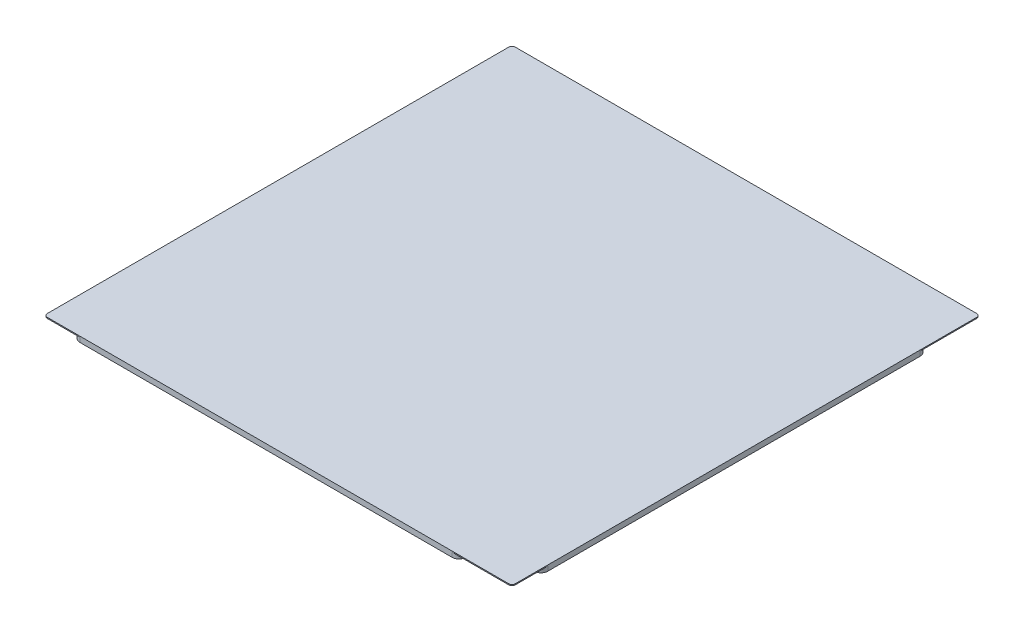
SolidWorks part; units mm, degrees
material "Kapton"
ref_plane "Front Plane" through (0, 0, 0) normal (0, 0, 1) x (1, 0, 0)
ref_plane "Top Plane" through (0, 0, 0) normal (0, 1, 0) x (1, 0, 0)
ref_plane "Right Plane" through (0, 0, 0) normal (1, 0, 0) x (0, 0, -1)
sketch "Sketch1" plane through (0, 0, 0) normal (0, 1, 0) x (1, 0, 0)
  line L1 (-68.5, -68.5) -> (68.5, -68.5)
  line L2 (-68.5, -68.5) -> (-68.5, 68.5)
  line L3 (-68.5, 68.5) -> (68.5, 68.5)
  line L4 (68.5, -68.5) -> (68.5, 68.5)
  line L5 (-68.5, -68.5) -> (68.5, 68.5) construction
  line L6 (-68.5, 68.5) -> (68.5, -68.5) construction
  point P0 (0, 0)
  dimension "D1" = 137
extrude "Boss-Extrude1" add sketch "Sketch1" along normal mid plane 0.3
sketch "Sketch2" plane through (0, -0.15, 0) normal (0, -1, 0) x (1, 0, 0)
  line L0 (70, -68.5) -> (50, -68.5) construction
  line L1 (68.5, -68.5) -> (-68.5, -68.5) construction
  line L2 (50, -68.5) -> (10, -68.5) construction
  line L3 (10, -68.5) -> (-10, -68.5) construction
  line L4 (-10, -68.5) -> (-50, -68.5) construction
  line L5 (-50, -68.5) -> (-70, -68.5) construction
  line L6 (50, -68.5) -> (60, -55) construction
  line L7 (-68.5, -68.5) -> (-68.5, 68.5) construction
  line L8 (68.5, 68.5) -> (68.5, -68.5) construction
  line L9 (-55, -60) -> (-68.5, -60)
  line L10 (60, -55) -> (-53, -55)
  line L11 (60, -55) -> (60, -68.5)
  line L12 (60, -68.5) -> (-53, -68.5)
  line L13 (-53, -55) -> (-53, -68.5)
  line L14 (-55, -60) -> (-55, 53)
  line L15 (-55, 53) -> (-68.5, 53)
  line L16 (-68.5, -60) -> (-68.5, 53)
  line L17 (-60, 55) -> (-60, 68.5)
  line L18 (-60, 55) -> (53, 55)
  line L19 (53, 55) -> (53, 68.5)
  line L20 (-60, 68.5) -> (53, 68.5)
  line L21 (55, 60) -> (68.5, 60)
  line L22 (55, 60) -> (55, -53)
  line L23 (55, -53) -> (68.5, -53)
  line L24 (68.5, 60) -> (68.5, -53)
  line L25 (-68.5, 68.5) -> (68.5, 68.5) construction
  point P33 (0, 0)
  dimension "D1" = 40
  dimension "D2" = 13.5
  dimension "D3" = 10
  dimension "D4" = 1.5
  dimension "D5" = 1.5
  dimension "D6" = 3
  dimension "D7" = 4
extrude "Boss-Extrude2" add sketch "Sketch2" along normal blind 1.3
fillet "Fillet1" radius 2 16 edges at (60, -0.8, -55) (-53, -0.8, -55) (-53, -0.8, -68.5) (-68.5, -0.8, -60) (-55, -0.8, -60) (-55, -0.8, 53) (-68.5, -0.8, 53) (-60, -0.8, 68.5) (-60, -0.8, 55) (53, -0.8, 55) (53, -0.8, 68.5) (60, -0.8, -68.5) (55, -0.8, 60) (68.5, -0.8, 60) (68.5, -0.8, -53) (55, -0.8, -53)
fillet "Fillet2" radius 1 4 edges at (-68.5, 0, 68.5) (-68.5, 0, -68.5) (68.5, 0, -68.5) (68.5, 0, 68.5)
equation "\"panel_width\"= 140mm"
equation "\"finger_joint_width\" = 40mm"
equation "\"D1@Sketch1\"=\"panel_width\"-3"
equation "\"D1@Sketch2\"=\"finger_joint_width\""
